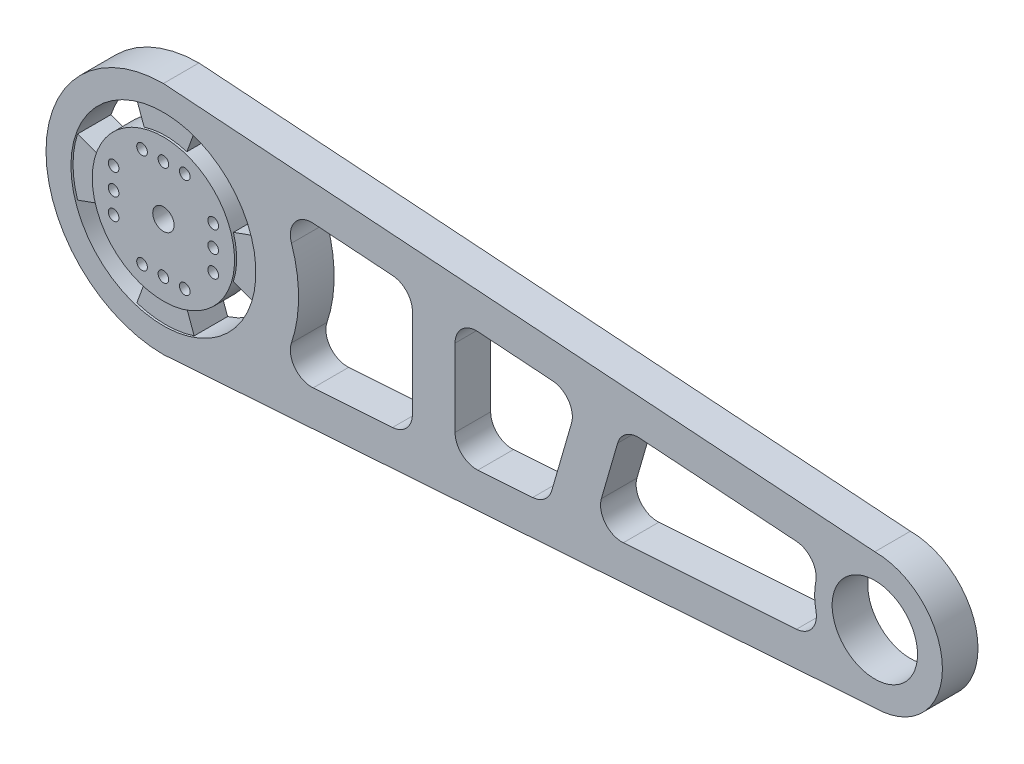
SolidWorks part; units mm, degrees
ref_plane "前视基准面" through (0, 0, 0) normal (0, 0, 1) x (1, 0, 0)
ref_plane "上视基准面" through (0, 0, 0) normal (0, 1, 0) x (1, 0, 0)
ref_plane "右视基准面" through (0, 0, 0) normal (1, 0, 0) x (0, 0, -1)
sketch "草图1" plane through (0, 0, 0) normal (0, 0, 1) x (1, 0, 0)
  line L0 (64.9709, 0) -> (-77.7905, 0) construction
  line L7 (-67.3514, 16.5) -> (32.6486, 9.5)
  line L8 (-67.3514, -16.5) -> (32.6486, -9.5)
  circle A2 centre (32.6486, 0) radius 6
  arc A4 (32.6486, -9.5) -> (32.6486, 9.5) centre (32.6486, 0) ccw
  arc A5 (-67.3514, 16.5) -> (-67.3514, -16.5) centre (-67.3514, 0) ccw
  point P3 (0, 0)
  dimension "D1" = 33
  dimension "D2" = 12
  dimension "D5" = 19
  dimension "D4" = 100
extrude "凸台-拉伸1" add sketch "草图1" along normal blind 5
sketch "草图2" plane through (0, 0, 0) normal (0, 0, -1) x (-1, 0, 0)
  line L0 (48.7055, 0) -> (85.8742, 0) construction
  line L1 (67.3514, 18.5813) -> (67.3514, -18.0319) construction
  line L2 (57.8849, 10) -> (77.3514, 10) construction
  line L3 (70.3514, 9.5394) -> (71.3783, 12.3606)
  line L4 (64.3514, 9.5394) -> (63.3246, 12.3606)
  line L5 (76.8908, 3) -> (79.712, 4.0268)
  line L6 (76.8908, -3) -> (79.712, -4.0268)
  line L7 (70.3514, -9.5394) -> (71.3783, -12.3606)
  line L8 (64.3514, -9.5394) -> (63.3246, -12.3606)
  line L9 (57.812, -3) -> (54.9908, -4.0268)
  line L10 (57.812, 3) -> (54.9908, 4.0268)
  line L11 (60.3514, -3) -> (60.3514, 4.0268) construction
  arc A0 (63.3246, 12.3606) -> (54.9908, 4.0268) centre (67.3514, 0) ccw
  arc A1 (64.3514, 9.5394) -> (57.812, 3) centre (67.3514, 0) ccw
  arc A2 (57.812, -3) -> (64.3514, -9.5394) centre (67.3514, 0) ccw
  arc A3 (54.9908, -4.0268) -> (63.3246, -12.3606) centre (67.3514, 0) ccw
  arc A4 (70.3514, -9.5394) -> (76.8908, -3) centre (67.3514, 0) ccw
  arc A5 (71.3783, -12.3606) -> (79.712, -4.0268) centre (67.3514, 0) ccw
  arc A6 (76.8908, 3) -> (70.3514, 9.5394) centre (67.3514, 0) ccw
  arc A7 (79.712, 4.0268) -> (71.3783, 12.3606) centre (67.3514, 0) ccw
  circle A12 centre (67.3514, 0) radius 1.5
  circle A13 centre (60.3514, 0) radius 0.75
  circle A14 centre (67.3514, 0) radius 10 construction
  circle A15 centre (60.3514, 3) radius 0.75
  circle A16 centre (60.3514, -3) radius 0.75
  circle A17 centre (70.3514, 7) radius 0.75
  circle A18 centre (67.3514, 7) radius 0.75
  circle A19 centre (64.3514, 7) radius 0.75
  circle A20 centre (74.3514, -3) radius 0.75
  circle A21 centre (74.3514, 0) radius 0.75
  circle A22 centre (74.3514, 3) radius 0.75
  circle A23 centre (64.3514, -7) radius 0.75
  circle A24 centre (67.3514, -7) radius 0.75
  circle A25 centre (70.3514, -7) radius 0.75
  point P30 (67.3514, 0)
  point P37 (67.3514, 0)
  point P58 (67.3514, 0)
  dimension "D1" = 26
  dimension "D2" = 20
  dimension "D4" = 110
  dimension "D6" = 1.5
  dimension "D9" = 3
  dimension "D10" = 1.5
  dimension "D7" = 7
  dimension "D8" = 1.5
  dimension "D3" = 3
  dimension "D11" = 3
  dimension "D12" = 3
  dimension "D5" = 4
  dimension "D13" = 4
extrude "切除-拉伸3" cut sketch "草图2" against normal through all
sketch "草图7" plane through (0, 0, 5) normal (0, 0, 1) x (1, 0, 0)
  line L0 (-101.7656, 0) -> (74.4294, 0) construction
  line L1 (-32.3514, 6.2404) -> (-32.3514, -6.2799)
  line L2 (-35.1419, 9.2331) -> (-46.2923, 10.0136)
  line L3 (32.6486, 9.5) -> (-67.3514, 16.5) construction
  line L7 (-35.1492, -9.2731) -> (-46.3039, -10.0269)
  line L8 (-23.1419, 8.3931) -> (-12.6586, 7.6593)
  line L9 (-23.1492, -8.4622) -> (-15.4473, -7.9417)
  line L10 (-26.3514, -5.469) -> (-26.3514, 5.4004)
  line L11 (-12.7677, -5.7822) -> (-9.9862, 3.8329)
  line L12 (-3.5059, 4.6432) -> (-5.7903, -3.2539)
  line L13 (-2.7062, -7.0807) -> (21.637, -5.4357)
  line L14 (-0.4145, 6.8022) -> (21.6093, 5.2605)
  arc A0 (-49.3487, -6.0746) -> (-49.345, 6.0635) centre (-67.3514, 0) ccw
  arc A5 (24.3457, 1.7009) -> (24.372, -1.8319) centre (33.1835, 0) ccw
  arc A6 (24.3457, 1.7009) -> (21.6093, 5.2605) centre (21.3998, 2.2678) ccw
  arc A7 (21.637, -5.4357) -> (24.372, -1.8319) centre (21.4348, -2.4425) ccw
  arc A8 (-2.7062, -7.0807) -> (-5.7903, -3.2539) centre (-2.9085, -4.0875) cw
  arc A9 (-0.4145, 6.8022) -> (-3.5059, 4.6432) centre (-0.624, 3.8095) ccw
  arc A10 (-9.9862, 3.8329) -> (-12.6586, 7.6593) centre (-12.8681, 4.6666) ccw
  arc A11 (-12.7677, -5.7822) -> (-15.4473, -7.9417) centre (-15.6495, -4.9485) cw
  arc A12 (-26.3514, -5.469) -> (-23.1492, -8.4622) centre (-23.3514, -5.469) ccw
  arc A13 (-26.3514, 5.4004) -> (-23.1419, 8.3931) centre (-23.3514, 5.4004) cw
  arc A14 (-32.3514, -6.2799) -> (-35.1492, -9.2731) centre (-35.3514, -6.2799) cw
  arc A15 (-32.3514, 6.2404) -> (-35.1419, 9.2331) centre (-35.3514, 6.2404) ccw
  arc A16 (-46.3039, -10.0269) -> (-49.3487, -6.0746) centre (-46.5061, -7.0337) cw
  arc A17 (-46.2923, 10.0136) -> (-49.345, 6.0635) centre (-46.5018, 7.021) ccw
  point P32 (-13.3514, -7.8001)
  point P35 (-26.3514, -8.6786)
  dimension "D1" = 38
  dimension "D2" = 35
  dimension "D8" = 18
  dimension "D9" = 3
  dimension "D10" = 3
  dimension "D3" = 5
  dimension "D4" = 6
  dimension "D5" = 110
  dimension "D6" = 6
  dimension "D7" = 13
extrude "切除-拉伸8" cut sketch "草图7" against normal through all
sketch "草图8" plane through (0, 0, 0) normal (0, 0, -1) x (-1, 0, 0)
  circle A1 centre (67.3514, 0) radius 10
extrude "切除-拉伸9" cut sketch "草图8" against normal blind 2
sketch "草图9" plane through (0, 0, 5) normal (0, 0, 1) x (1, 0, 0)
  line L0 (-71.3783, 12.3606) -> (-70.3514, 9.5394) construction
  line L1 (-64.3514, 9.5394) -> (-63.3246, 12.3606) construction
  line L2 (-71.3783, 12.3606) -> (-70.3514, 9.5394)
  line L3 (-64.3514, 9.5394) -> (-63.3246, 12.3606)
  line L4 (-63.3246, -12.3606) -> (-64.3514, -9.5394) construction
  line L5 (-70.3514, -9.5394) -> (-71.3783, -12.3606) construction
  line L6 (-79.712, -4.0268) -> (-76.8908, -3) construction
  line L7 (-76.8908, 3) -> (-79.712, 4.0268) construction
  line L8 (-57.812, -3) -> (-54.9908, -4.0268) construction
  line L9 (-54.9908, 4.0268) -> (-57.812, 3) construction
  line L10 (-63.3246, -12.3606) -> (-64.3514, -9.5394)
  line L11 (-70.3514, -9.5394) -> (-71.3783, -12.3606)
  line L12 (-79.712, -4.0268) -> (-76.8908, -3)
  line L13 (-76.8908, 3) -> (-79.712, 4.0268)
  line L14 (-57.812, -3) -> (-54.9908, -4.0268)
  line L15 (-54.9908, 4.0268) -> (-57.812, 3)
  line L16 (-64.3514, -9.5394) -> (-63.3246, -12.3606)
  arc A0 (-79.712, 4.0268) -> (-79.712, -4.0268) centre (-67.3514, 0) ccw
  arc A1 (-76.8908, 3) -> (-76.8908, -3) centre (-67.3514, 0) ccw
  arc A2 (-64.3514, 9.5394) -> (-70.3514, 9.5394) centre (-67.3514, 0) ccw
  arc A3 (-63.3246, 12.3606) -> (-71.3783, 12.3606) centre (-67.3514, 0) ccw
  arc A4 (-54.9908, -4.0268) -> (-54.9908, 4.0268) centre (-67.3514, 0) ccw
  arc A5 (-71.3783, -12.3606) -> (-63.3246, -12.3606) centre (-67.3514, 0) ccw
  arc A6 (-70.3514, -9.5394) -> (-64.3514, -9.5394) centre (-67.3514, 0) ccw
  arc A7 (-57.812, -3) -> (-57.812, 3) centre (-67.3514, 0) ccw
extrude "切除-拉伸10" cut sketch "草图9" against normal blind 0.3 contours L3 A3 L2 A2 | A7 L14 A4 L15 | A6 L11 A5 L10 | A1 L13 A0 L12
